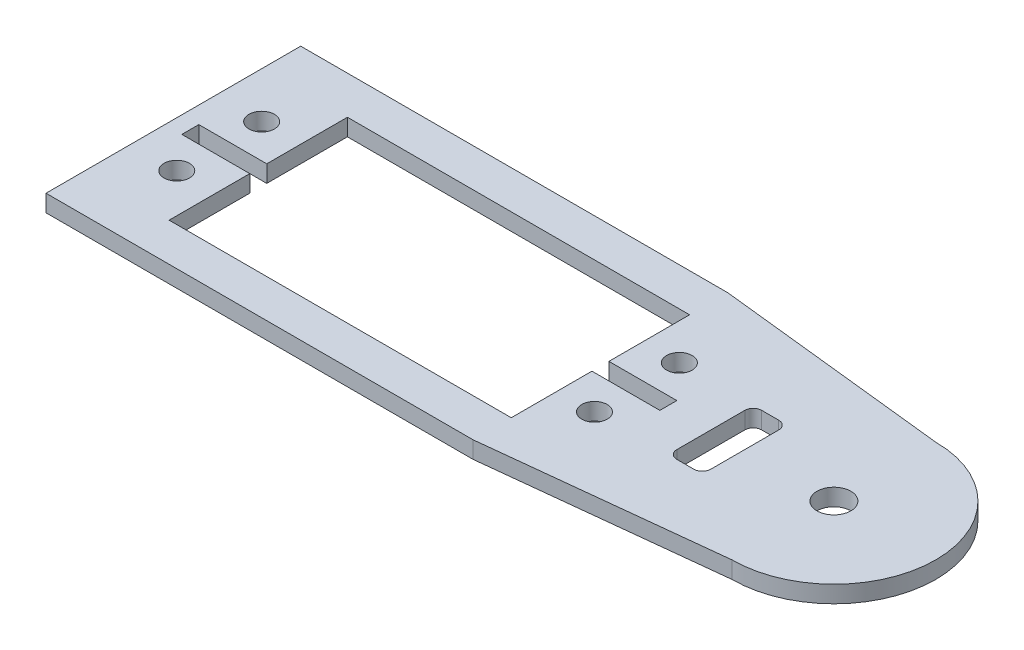
SolidWorks part; units mm, degrees
ref_plane "Спереди" through (0, 0, 0) normal (0, 0, 1) x (1, 0, 0)
ref_plane "Сверху" through (0, 0, 0) normal (0, 1, 0) x (1, 0, 0)
ref_plane "Справа" through (0, 0, 0) normal (1, 0, 0) x (0, 0, -1)
sketch "Эскиз1" plane through (0, 0, 0) normal (0, 1, 0) x (1, 0, 0)
  line L0 (3.4, 10) -> (3.4, 21.5) construction
  line L1 (0, 0) -> (93, 0) construction
  line L2 (0, 0) -> (0, 30) construction
  line L3 (0, 30) -> (93, 30) construction
  line L4 (93, 0) -> (93, 30) construction
  line L5 (8, 25.5) -> (48.3, 25.5)
  line L6 (8, 25.5) -> (8, 4.5) construction
  line L7 (8, 4.5) -> (48.3, 4.5)
  line L8 (48.3, 25.5) -> (48.3, 16)
  line L9 (1.9, 10) -> (1.9, 20) construction
  line L10 (3.4, 10) -> (54.1, 10) construction
  line L11 (3.4, 20) -> (54.1, 20) construction
  line L12 (3.4, 8.5) -> (52.6, 8.5) construction
  line L13 (52.6, 10) -> (52.6, 21.5) construction
  line L14 (54.1, 10) -> (54.1, 20) construction
  line L15 (0, 16) -> (8, 16)
  line L16 (0, 14) -> (8, 14)
  line L17 (56.3, 14) -> (56.3, 16)
  line L18 (48.3, 14) -> (48.3, 4.5)
  line L19 (48.3, 16) -> (56.3, 16)
  line L20 (48.3, 14) -> (56.3, 14)
  line L21 (8, 4.5) -> (8, 14)
  line L22 (8, 16) -> (8, 25.5)
  line L23 (0, 14) -> (0, 16)
  line L24 (-2, 30) -> (48.3, 30)
  line L25 (48.3, 30) -> (75.8, 27)
  line L26 (-2, 30) -> (-2, 0)
  line L27 (-2, 0) -> (48.3, 0)
  line L28 (48.3, 0) -> (75.8, 3)
  line L29 (-2, 15) -> (87.8, 15) construction
  line L30 (65.3, 20) -> (61.3, 20)
  line L31 (65.3, 20) -> (65.3, 10)
  line L32 (65.3, 10) -> (61.3, 10)
  line L33 (61.3, 20) -> (61.3, 10)
  circle A0 centre (3.4, 10) radius 1.5
  circle A1 centre (3.4, 20) radius 1.5
  circle A2 centre (52.6, 10) radius 1.5
  circle A3 centre (52.6, 20) radius 1.5
  circle A4 centre (75.8, 15) radius 2
  arc A6 (75.8, 3) -> (75.8, 27) centre (75.8, 15) ccw
  point P9 (8, 15)
  point P10 (0, 15)
  point P38 (93, 15)
  point P50 (61.3, 15)
  dimension "D6" = 3
  dimension "D9" = 10
  dimension "D10" = 49.2
  dimension "D11" = 1
  dimension "D13" = 4
  dimension "D15" = 12
  dimension "D1" = 93
  dimension "D2" = 30
  dimension "D3" = 40.3
  dimension "D4" = 21
  dimension "D5" = 8
  dimension "D7" = 3.4
  dimension "D8" = 5
  dimension "D12" = 2
  dimension "D14" = 27.5
  dimension "D16" = 77.8
  dimension "D17" = 50.3
  dimension "D18" = 50.3
  dimension "D19" = 4
  dimension "D20" = 10
  dimension "D21" = 8
  dimension "D22" = 5
extrude "Бобышка-Вытянуть1" add sketch "Эскиз1" along normal blind 2
sketch "Эскиз2" plane through (0, 2, 0) normal (0, 1, 0) x (1, 0, 0)
  point P0 (75.8, 15)
fillet "Скругление1" radius 1 4 edges at (61.3, 1, -10) (65.3, 1, -10) (61.3, 1, -20) (65.3, 1, -20)
